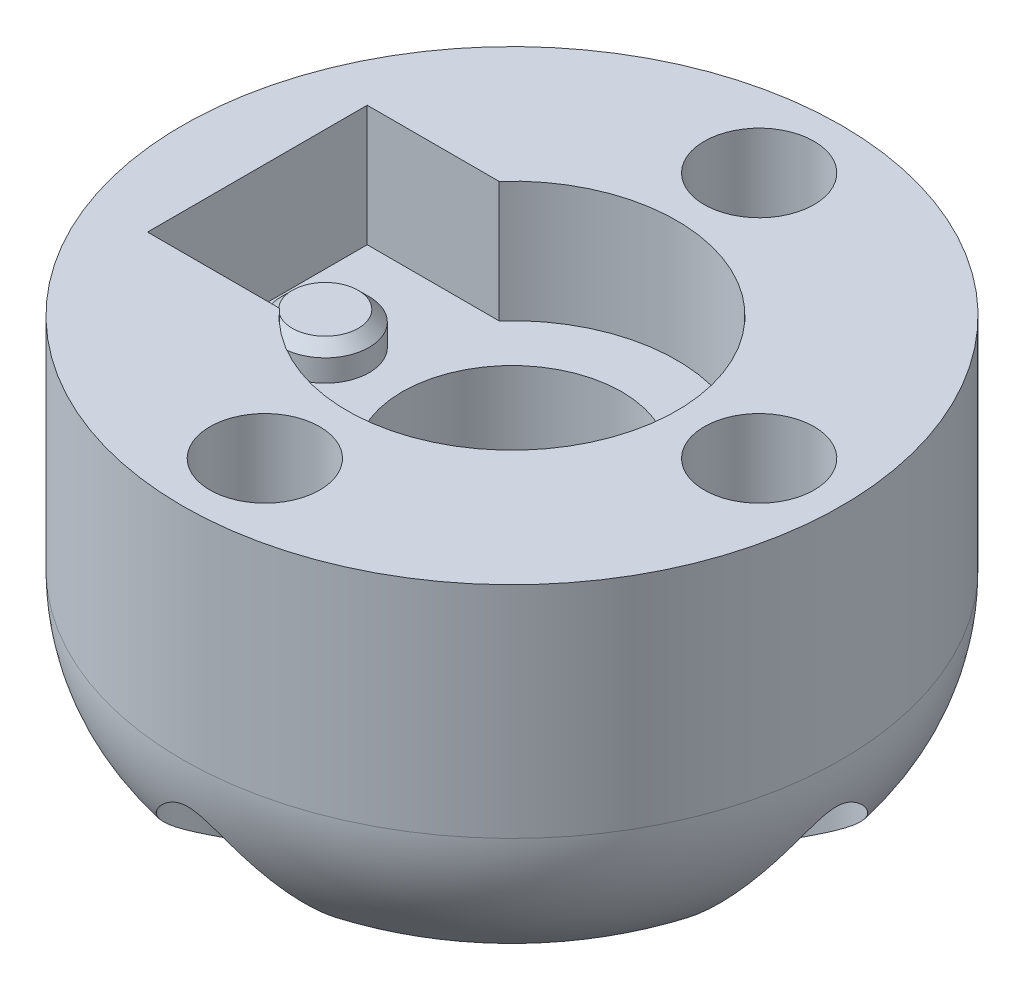
SolidWorks part; units mm, degrees
material "AISI 304"
ref_plane "Front Plane" through (0, 0, 0) normal (0, 0, 1) x (1, 0, 0)
ref_plane "Top Plane" through (0, 0, 0) normal (0, 1, 0) x (1, 0, 0)
ref_plane "Right Plane" through (0, 0, 0) normal (1, 0, 0) x (0, 0, -1)
sketch "Sketch1" plane through (0, 0, 0) normal (0, 1, 0) x (1, 0, 0)
  circle A0 centre (0, 0) radius 15
  circle A1 centre (0, 0) radius 5
  dimension "D1" = 30
  dimension "D2" = 10
extrude "Boss-Extrude1" add sketch "Sketch1" along normal blind 7.5
sketch "Sketch2" plane through (0, 7.5, 0) normal (0, 1, 0) x (1, 0, 0)
  circle A0 centre (0, 0) radius 15
  circle A1 centre (0, 0) radius 7.5
  circle A2 centre (0, 0) radius 15 construction
  dimension "D1" = 15
extrude "Boss-Extrude2" add sketch "Sketch2" along normal blind 5.5
sketch "Sketch3" plane through (0, 0, 0) normal (0, -1, 0) x (1, 0, 0)
  circle A0 centre (0, 0) radius 15
  circle A1 centre (0, 0) radius 15 construction
  point P6 (0, 0)
extrude "Boss-Extrude3" add sketch "Sketch3" along normal blind 5
sketch "Sketch4" plane through (0, -5, 0) normal (0, -1, 0) x (-1, 0, 0)
  point P0 (0, 0)
hole_wizard "M4x0.7 Tapped Hole1" positions "Sketch4" profile "Sketch5" tap size "M4x0.7" standard "ANSI Metric" end condition through all
cosmetic thread "Hole Thread1" parameters "D2"=4
sketch "Sketch5" plane through (0, -5, 0) normal (1, 0, 0) x (0, 0, -1)
  line L0 (0, 0) -> (0, 18)
  line L1 (0, 18) -> (1.65, 18)
  line L2 (1.65, 18) -> (1.65, 0)
  line L5 (1.65, 0) -> (0, 0)
  line L11 (0, -6.35) -> (0, 107.95) construction
  dimension "Thru Tap Drill Dia." = 3.3
  dimension "Thru Tap Drill Depth" = 18
fillet "Fillet1" radius 8 1 edges at (0, -5, -15)
sketch "Sketch6" plane through (0, -5, 0) normal (0, -1, 0) x (1, 0, 0)
  circle A0 centre (0, 0) radius 11.25 construction
  point P0 (0, 11.25)
  point P1 (11.25, 0)
  point P2 (0, -11.25)
  dimension "D1" = 22.5
sketch "Sketch7" plane through (0, -5, 0) normal (0, -1, 0) x (-1, 0, 0)
  point P0 (0, 11.25)
  point P3 (-11.25, 0)
  point P6 (0, -11.25)
hole_wizard "Hole1" positions "Sketch7" profile "Sketch8" legacy end condition through all
sketch "Sketch8" plane through (0, -5, -11.25) normal (1, 0, 0) x (0, 0, -1)
  line L0 (0, 0) -> (0, 19.5022)
  line L1 (0, 19.5022) -> (2.5, 18)
  line L2 (2.5, 18) -> (2.5, 7)
  line L3 (2.5, 7) -> (3.5, 7)
  line L4 (3.5, 0) -> (0, 0)
  line L5 (0, -11.3109) -> (0, 121.1557) construction
  line L6 (0, 19.5022) -> (-2.5, 18) construction
  line L7 (3.5, 7) -> (3.5, 0)
  dimension "Depth" = 18
  dimension "Drill Angle" = 118
  dimension "Diameter" = 5
  dimension "C-Bore Diameter" = 7
  dimension "C-Bore Depth" = 7
sketch "Sketch9" plane through (0, 13, 0) normal (0, 1, 0) x (1, 0, 0)
  line L0 (-5.5902, 5) -> (-11.5902, 5)
  line L1 (-11.5902, 5) -> (-11.5902, -5)
  line L2 (-11.5902, -5) -> (-5.5902, -5)
  circle A0 centre (0, 0) radius 7.5 construction
  circle A1 centre (0, 0) radius 7.5 construction
  arc A2 (-5.5902, 5) -> (-5.5902, -5) centre (0, 0) ccw
  dimension "D1" = 10
  dimension "D2" = 6
extrude "Cut-Extrude1" cut sketch "Sketch9" against normal up to surface (5.5 mm away) up to face at (0, 7.5, 5)
sketch "Sketch10" plane through (0, 7.5, 0) normal (0, 1, 0) x (1, 0, 0)
  circle A0 centre (-8.5, 0) radius 2
  dimension "D1" = 4
  dimension "D2" = 8.5
extrude "Boss-Extrude4" add sketch "Sketch10" along normal blind 1.5
chamfer "Chamfer1" distance 0.5 angle 45 1 edges at (-8.5, 9, 2)
